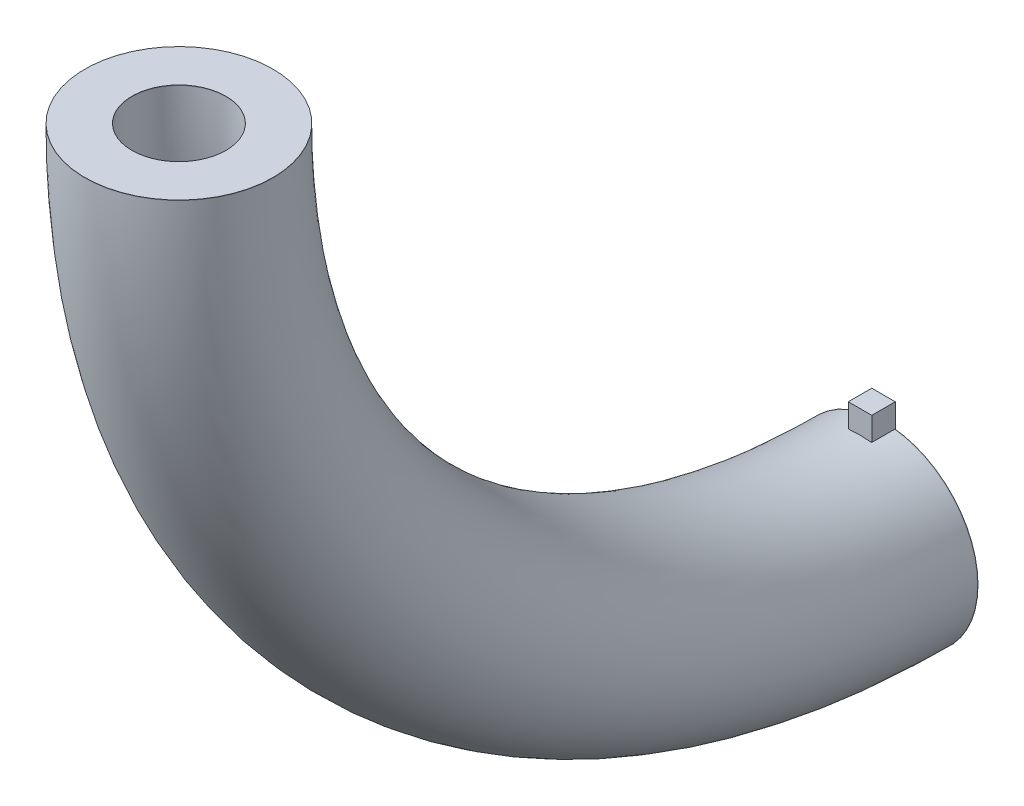
SolidWorks part; units mm, degrees
ref_plane "Front Plane" through (0, 0, 0) normal (0, 0, 1) x (1, 0, 0)
ref_plane "Top Plane" through (0, 0, 0) normal (0, 1, 0) x (1, 0, 0)
ref_plane "Right Plane" through (0, 0, 0) normal (1, 0, 0) x (0, 0, -1)
sketch "Sketch1" plane through (0, 0, 0) normal (0, 0, 1) x (1, 0, 0)
  circle A0 centre (0, 0) radius 2
  circle A1 centre (0, 0) radius 1
  dimension "D1" = 4
  dimension "D2" = 1
sketch "Sketch2" plane through (0, 0, 0) normal (1, 0, 0) x (0, 0, -1)
  line L0 (0, 0) -> (-0.01, 0)
  line L1 (-15, 14.99) -> (-15, 15)
  arc A0 (-0.01, 0) -> (-15, 14.99) centre (-0.01, 14.99) cw
  point P6 (-15, 0)
  dimension "D3" = 14.99
  dimension "D1" = 15
  dimension "D2" = 15
sweep "Sweep1" add profiles "Sketch1" path "Sketch2"
sketch "Sketch3" plane through (0, 0, 0) normal (1, 0, 0) x (0, 0, -1)
  line L1 (-0.01, 2) -> (-0.51, 2)
  line L2 (-0.01, 2) -> (-0.01, 2.5)
  line L3 (-0.01, 2.5) -> (-0.51, 2.5)
  line L4 (-0.51, 2) -> (-0.51, 2.5)
  dimension "D1" = 0.5
  dimension "D2" = 0.5
extrude "Boss-Extrude1" add sketch "Sketch3" along normal mid plane 0.5
